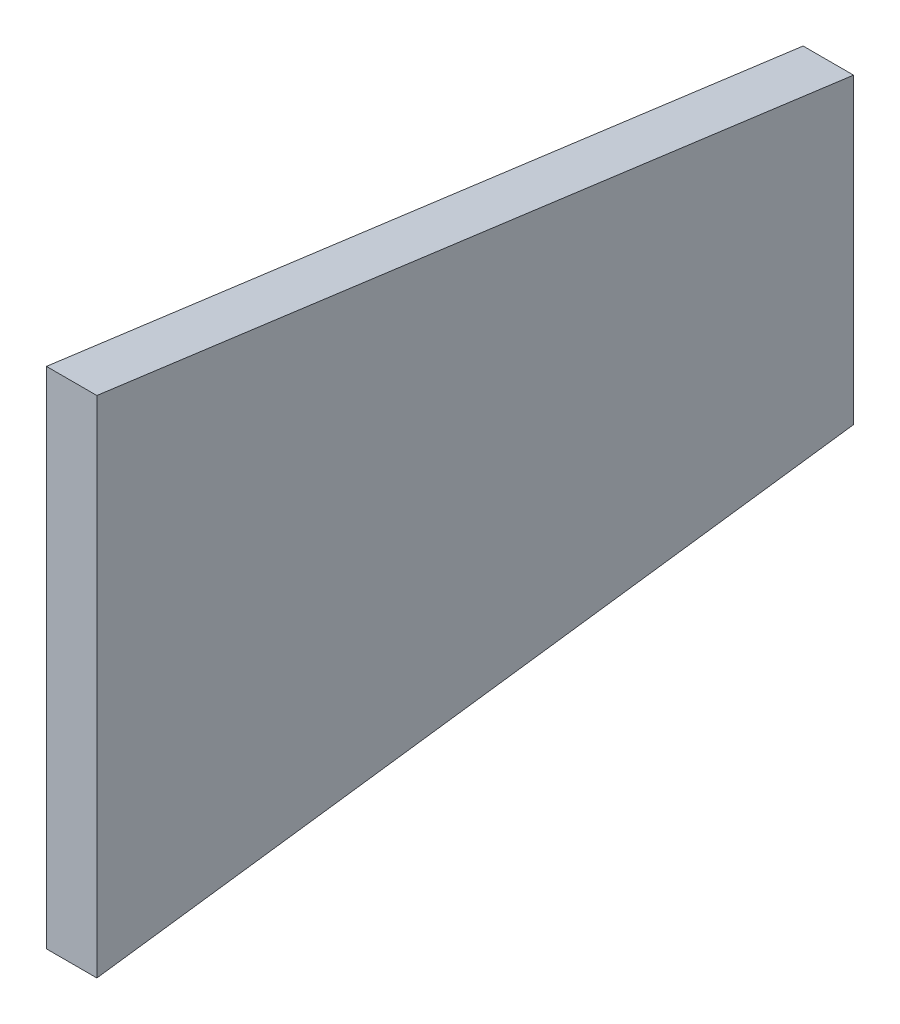
SolidWorks part; units mm, degrees
ref_plane "Ön Düzlem" through (0, 0, 0) normal (0, 0, 1) x (1, 0, 0)
ref_plane "Üst Düzlem" through (0, 0, 0) normal (0, 1, 0) x (1, 0, 0)
ref_plane "Sağ Düzlem" through (0, 0, 0) normal (1, 0, 0) x (0, 0, -1)
sketch "Sketch1" plane through (0, 0, 0) normal (1, 0, 0) x (0, 0, -1)
  line L0 (0, 0) -> (150, -20)
  line L1 (150, -20) -> (150, -80)
  line L2 (150, -80) -> (0, -100)
  line L3 (0, -100) -> (0, 0)
  point P3 (150, -50)
  dimension "D1" = 150
  dimension "D2" = 60
  dimension "D3" = 50
  dimension "D4" = 100
extrude "Boss-Extrude1" add sketch "Sketch1" along normal blind 10
sketch "Sketch2" plane through (10, 0, 0) normal (1, 0, 0) x (0, 0, -1)
  line L0 (150, -50) -> (0, -50) construction
  line L1 (150, -80) -> (150, -20) construction
  line L2 (0, 0) -> (0, -100) construction
sketch "Sketch3" plane through (0, 0, 0) normal (-1, 0, 0) x (0, 0, 1)
  line L0 (0, -50) -> (-150, -50) construction
  line L1 (0, 0) -> (0, -100) construction
  line L2 (-150, -80) -> (-150, -20) construction
sketch "Sketch4" plane through (0, 0, 0) normal (-1, 0, 0) x (0, 0, 1)
  line L0 (0, -50) -> (-150, -50) construction
  line L1 (0, 0) -> (0, -100) construction
  line L2 (-150, -80) -> (-150, -20) construction
sketch "Sketch5" plane through (10, 0, 0) normal (1, 0, 0) x (0, 0, -1)
  line L0 (150, -50) -> (0, -50) construction
  line L1 (150, -80) -> (150, -20) construction
  line L2 (0, 0) -> (0, -100) construction
sketch "Sketch6" plane through (0, 0, 0) normal (-1, 0, 0) x (0, 0, 1)
  line L0 (-150, -50) -> (0, -50) construction
  line L1 (-150, -80) -> (-150, -20) construction
  line L2 (0, 0) -> (0, -100) construction
sketch "Sketch7" plane through (10, 0, 0) normal (1, 0, 0) x (0, 0, -1)
  line L0 (150, -50) -> (0, -50) construction
  line L1 (150, -80) -> (150, -20) construction
  line L2 (0, 0) -> (0, -100) construction
